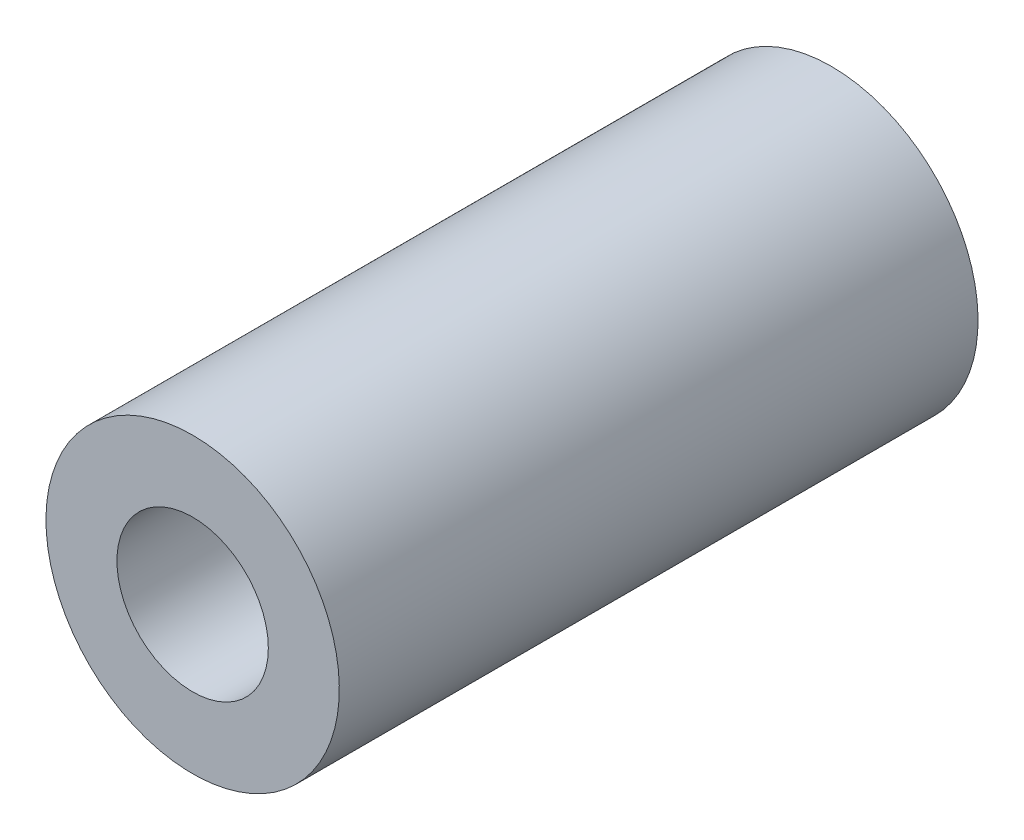
SolidWorks part; units mm, degrees
material "PET"
ref_plane "Front Plane" through (0, 0, 0) normal (1, 0, 0) x (0, 1, 0)
ref_plane "Top Plane" through (0, 0, 0) normal (0, 0, 1) x (0, 1, 0)
ref_plane "Right Plane" through (0, 0, 0) normal (0, 1, 0) x (-1, 0, 0)
sketch "Sketch1" plane through (0, 0, 0) normal (0, 0, 1) x (0, 1, 0)
  circle A0 centre (0, 0) radius 1.6
  dimension "D1" = 3.2
extrude "Extrude-Thin1" add sketch "Sketch1" along normal blind 13.5 thin
